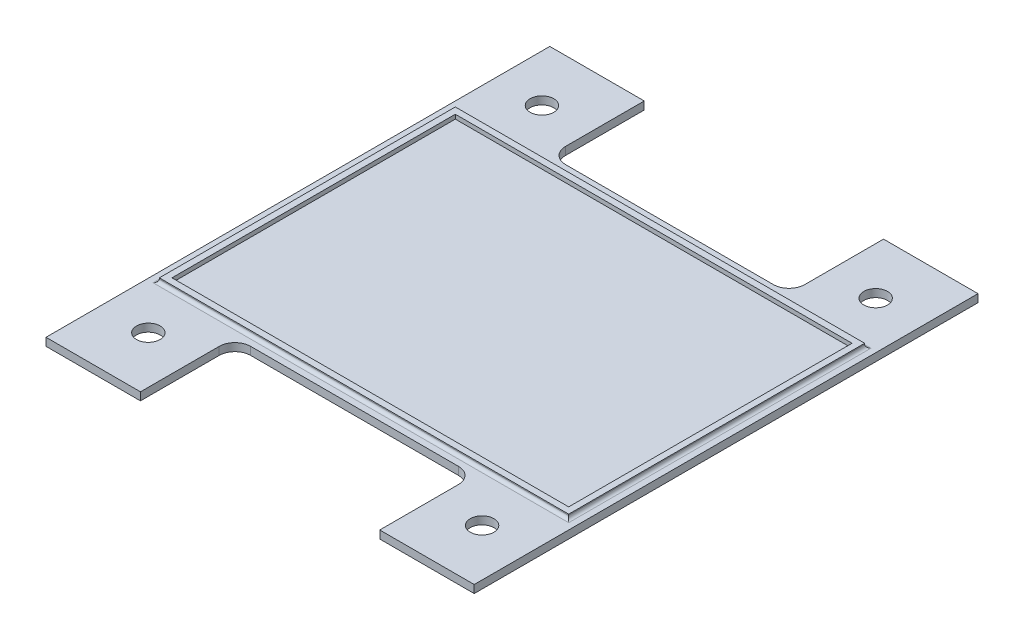
SolidWorks part; units mm, degrees
material "6061-T6 (SS)"
ref_plane "Front Plane" through (0, 0, 0) normal (0, 0, 1) x (1, 0, 0)
ref_plane "Top Plane" through (0, 0, 0) normal (0, 1, 0) x (1, 0, 0)
ref_plane "Right Plane" through (0, 0, 0) normal (1, 0, 0) x (0, 0, -1)
sketch "Sketch1" plane through (0, 0, 0) normal (0, 1, 0) x (1, 0, 0)
  line L1 (-86.36, -101.6) -> (86.36, -101.6)
  line L2 (-86.36, -101.6) -> (-86.36, 101.6)
  line L3 (-86.36, 101.6) -> (86.36, 101.6)
  line L4 (86.36, -101.6) -> (86.36, 101.6)
  line L5 (-86.36, -101.6) -> (86.36, 101.6) construction
  line L6 (-86.36, 101.6) -> (86.36, -101.6) construction
  point P0 (0, 0)
  dimension "D1" = 203.2
  dimension "D2" = 172.72
extrude "Boss-Extrude1" add sketch "Sketch1" along normal blind 3.175
sketch "Sketch2" plane through (0, 3.175, 0) normal (0, 1, 0) x (1, 0, 0)
  line L0 (86.36, 101.6) -> (-86.36, 101.6) construction
  line L1 (-48.26, 101.6) -> (48.26, 101.6)
  line L2 (-48.26, 101.6) -> (-48.26, 63.5)
  line L3 (-48.26, 63.5) -> (48.26, 63.5)
  line L4 (48.26, 101.6) -> (48.26, 63.5)
  line L5 (-86.36, -101.6) -> (86.36, -101.6) construction
  line L6 (-48.26, -101.6) -> (48.26, -101.6)
  line L7 (-48.26, -101.6) -> (-48.26, -63.5)
  line L8 (-48.26, -63.5) -> (48.26, -63.5)
  line L9 (48.26, -101.6) -> (48.26, -63.5)
  line L10 (0, 101.6) -> (0, -101.6) construction
  line L11 (-86.36, 0) -> (86.36, 0) construction
  line L12 (-86.36, 101.6) -> (-86.36, -101.6) construction
  line L13 (86.36, -101.6) -> (86.36, 101.6) construction
  point P20 (6.8305, -114.3)
  dimension "D1" = 127
  dimension "D2" = 38.1
extrude "Cut-Extrude1" cut sketch "Sketch2" against normal through all
fillet "Fillet1" radius 6.35 4 edges at (-48.26, 1.5875, -63.5) (48.26, 1.5875, -63.5) (48.26, 1.5875, 63.5) (-48.26, 1.5875, 63.5)
sketch "Sketch6" plane through (0, 3.175, 0) normal (0, 1, 0) x (1, 0, 0)
  line L0 (-80.01, -57.15) -> (-80.01, 57.15)
  line L1 (-82.55, -59.69) -> (82.55, -59.69)
  line L2 (-82.55, -59.69) -> (-82.55, 59.69)
  line L3 (-82.55, 59.69) -> (82.55, 59.69)
  line L4 (82.55, -59.69) -> (82.55, 59.69)
  line L5 (-82.55, -59.69) -> (82.55, 59.69) construction
  line L6 (-82.55, 59.69) -> (82.55, -59.69) construction
  line L7 (-80.01, 57.15) -> (80.01, 57.15)
  line L8 (80.01, -57.15) -> (80.01, 57.15)
  line L9 (-80.01, -57.15) -> (80.01, -57.15)
  point P0 (0, 0)
  dimension "D1" = 165.1
  dimension "D2" = 119.38
  dimension "D3" = 2.54
extrude "Boss-Extrude2" add sketch "Sketch6" along normal blind 1.7145
fillet "Fillet2" radius 1.27 4 edges at (82.55, 3.175, 0) (0, 3.175, 59.69) (0, 3.175, -59.69) (-82.55, 3.175, 0)
hole_wizard "3/8 (0.375) Diameter Hole1" positions "Sketch7" profile "Sketch8" hole size "3/8" standard "ANSI Inch" end condition up to next
sketch "Sketch7" plane through (0, 3.175, 0) normal (0, 1, 0) x (1, 0, 0)
  line L0 (-67.31, -79.375) -> (-67.31, -101.6) construction
  line L1 (-86.36, -101.6) -> (-48.26, -101.6) construction
  point P0 (-67.31, -79.375)
  dimension "D1" = 22.225
sketch "Sketch8" plane through (-67.31, 3.175, 79.375) normal (1, 0, 0) x (0, 0, 1)
  line L0 (0, 0) -> (0, 3.176)
  line L1 (0, 3.176) -> (4.7625, 3.176)
  line L2 (4.7625, 3.176) -> (4.7625, 0)
  line L5 (4.7625, 0) -> (0, 0)
  line L11 (0, -6.35) -> (0, 107.95) construction
  dimension "Thru Hole Dia." = 9.525
  dimension "Thru Hole Depth" = 3.176
mirror "Mirror4" about plane through (0, 0, 0) normal (0, 0, 1) of "3/8 (0.375) Diameter Hole1"
mirror "Mirror5" about plane through (0, 0, 0) normal (1, 0, 0) of "Mirror4", "3/8 (0.375) Diameter Hole1"
